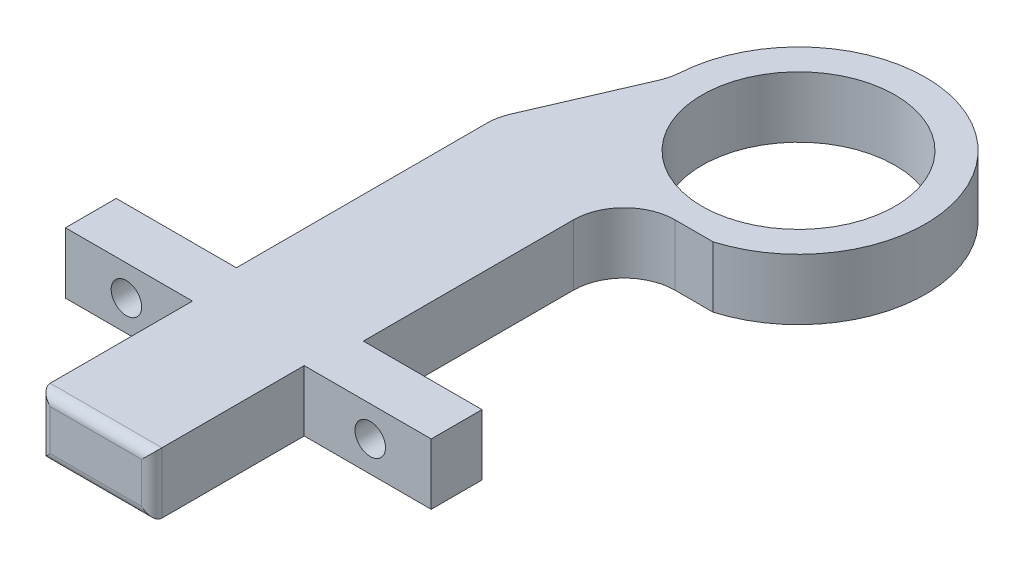
SolidWorks part; units mm, degrees
ref_plane "Alzado" through (0, 0, 0) normal (0, 0, 1) x (1, 0, 0)
ref_plane "Planta" through (0, 0, 0) normal (0, 1, 0) x (1, 0, 0)
ref_plane "Vista lateral" through (0, 0, 0) normal (1, 0, 0) x (0, 0, -1)
sketch "Croquis1" plane through (0, 0, 0) normal (0, 1, 0) x (1, 0, 0)
  line L0 (-12.5, 0) -> (-53.5222, 0) construction
  line L1 (0, 0) -> (-12.5, 21.6506) construction
  line L2 (-29.7673, 10.6211) -> (-25.3747, 20.7837)
  line L3 (-24, -36) -> (-24, -21) construction
  line L4 (-30.1777, -21) -> (-17.6777, -21)
  line L8 (-29.5, -21) -> (-18.5, -21)
  line L9 (-29.5, -21) -> (-29.5, -36)
  line L10 (-29.5, -36) -> (-18.5, -36)
  line L11 (-18.5, -21) -> (-18.5, -36)
  line L12 (-42, -16) -> (-27, -16) construction
  line L13 (-10.5, -16) -> (-6, -16) construction
  line L14 (-42, -16) -> (-27, -16)
  line L15 (-42, -16) -> (-42, -21)
  line L16 (-42, -21) -> (-30.1777, -21)
  line L18 (-6, -16) -> (-10.5, -16)
  line L19 (-6, -16) -> (-6, -21)
  line L20 (-6, -21) -> (-17.6777, -21)
  line L21 (-17.6777, -16) -> (-30.1777, -16)
  line L22 (-17.6777, -16) -> (-17.6777, 4.6717)
  line L23 (-17.6777, 9.6717) -> (-30.1777, 9.6717)
  line L24 (-30.1777, -16) -> (-30.1777, 8.6374)
  line L25 (-8.9286, 9.6717) -> (-12.6777, 9.6717)
  line L26 (-10.5, -16) -> (-17.6777, -16)
  arc A1 (-8.9286, 9.6717) -> (-24.9745, 22.4484) centre (-12.5, 21.6506) ccw
  circle A2 centre (-12.5, 21.6506) radius 9.5
  arc A6 (-30.1777, 8.6374) -> (-29.7673, 10.6211) centre (-25.1777, 8.6374) cw
  arc A7 (-24.9745, 22.4484) -> (-25.3747, 20.7837) centre (-29.9643, 22.7675) cw
  arc A8 (-17.6777, 4.6717) -> (-12.6777, 9.6717) centre (-12.6777, 4.6717) cw
  point P31 (-25, 21.6506)
  dimension "D3" = 25
  dimension "D4" = 5
  dimension "D5" = 19
  dimension "D6" = 21
  dimension "D1" = 25
  dimension "D2" = 60
  dimension "D7" = 11
  dimension "D8" = 15
  dimension "D9" = 24
  dimension "D10" = 5
  dimension "D11" = 18
  dimension "D12" = 18
extrude "Saliente-Extruir1" add sketch "Croquis1" along normal blind 6
sketch "Croquis2" plane through (0, 0, 21) normal (0, 0, 1) x (1, 0, 0)
  line L0 (-42, 3) -> (-6, 3) construction
  line L1 (-42, 6) -> (-42, 0) construction
  line L2 (-6, 6) -> (-6, 0) construction
  line L3 (-24, 6) -> (-24, 0) construction
  line L4 (-29.5, 6) -> (-18.5, 6) construction
  line L5 (-29.5, 0) -> (-18.5, 0) construction
  circle A0 centre (-36, 3) radius 1.5
  circle A1 centre (-12, 3) radius 1.5
  dimension "D3" = 3
  dimension "D4" = 3
  dimension "D1" = 12
  dimension "D2" = 12
extrude "Cortar-Extruir1" cut sketch "Croquis2" against normal blind 6
fillet "Redondeo1" radius 1 4 edges at (-29.5, 3, 36) (-18.5, 3, 36) (-24, 6, 36) (-24, 0, 36)
